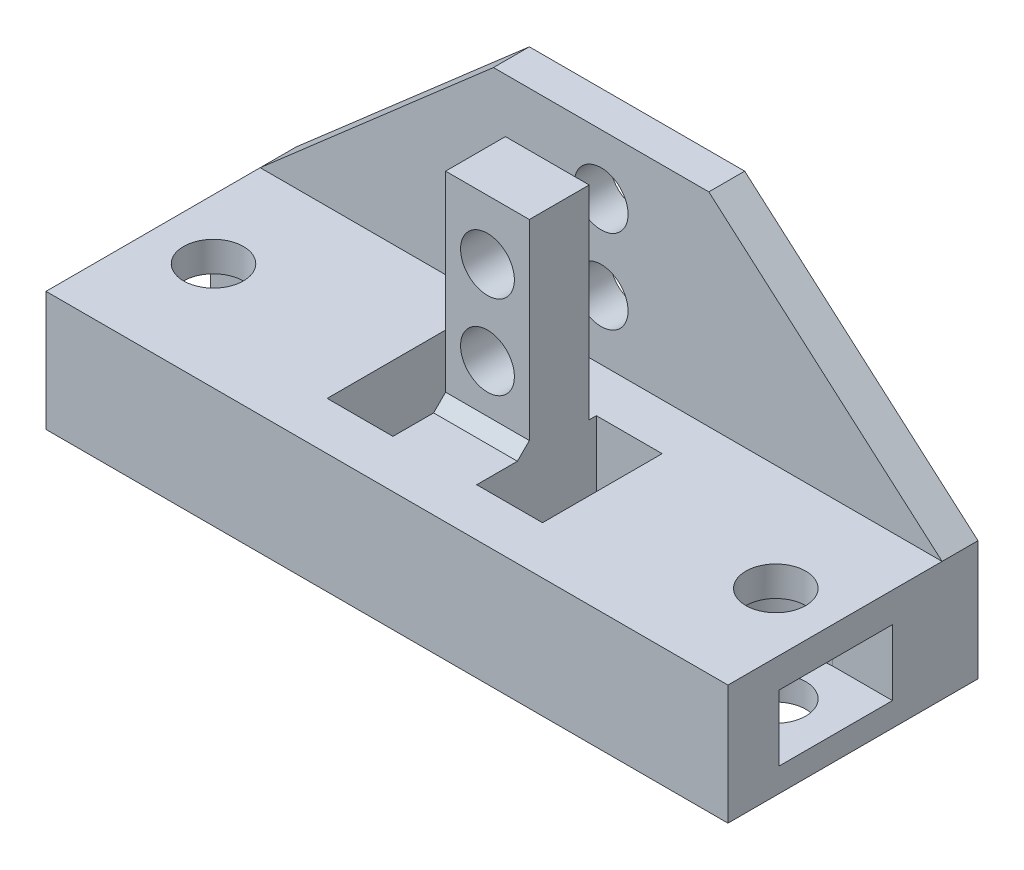
SolidWorks part; units mm, degrees
ref_plane "Plan de face" through (0, 0, 0) normal (0, 0, 1) x (1, 0, 0)
ref_plane "Plan de dessus" through (0, 0, 0) normal (0, 1, 0) x (1, 0, 0)
ref_plane "Plan de droite" through (0, 0, 0) normal (1, 0, 0) x (0, 0, -1)
sketch "Esquisse1" plane through (0, 0, 0) normal (0, 0, 1) x (1, 0, 0)
  line L0 (0, 17) -> (20, 17)
  line L1 (0, 0) -> (20, 0)
  line L2 (0, 0) -> (0, 25.6902)
  line L3 (0, 25.6902) -> (20, 25.6902)
  line L4 (20, 0) -> (20, 25.6902)
  circle A0 centre (10, 5) radius 2.1
  circle A1 centre (10, 12) radius 2.1
  dimension "D2" = 4.2
  dimension "D3" = 4.2
  dimension "D1" = 20
  dimension "D5" = 10
  dimension "D6" = 5
  dimension "D7" = 7
  dimension "D9" = 17
  dimension "D11" = 10
extrude "Boss.-Extru.1" add sketch "Esquisse1" along normal blind 5
sketch "Esquisse2" plane through (0, 0, 0) normal (0, -1, 0) x (1, 0, 0)
  line L0 (20, 5) -> (20, 0) construction
  line L1 (0, 0) -> (20, 0)
  line L2 (0, 0) -> (0, 5)
  line L3 (0, 5) -> (20, 5)
  line L4 (20, 0) -> (20, 5)
  line L5 (1, 5) -> (1, 0)
  line L6 (19, 5) -> (19, 0)
  line L7 (1, 3) -> (19, 3)
  line L9 (1, 0) -> (19, 0)
  line L10 (1, 0) -> (1, -5)
  line L11 (1, -5) -> (19, -5)
  line L12 (19, 0) -> (19, -5)
  line L13 (1, 0) -> (19, 0)
  line L14 (1, 0) -> (1, -0.6)
  line L15 (1, -0.6) -> (19, -0.6)
  line L16 (19, 0) -> (19, -0.6)
  point P11 (19, 2.5)
  dimension "D1" = 5
  dimension "D2" = 18
  dimension "D3" = 1
  dimension "D4" = 3
  dimension "D5" = 5
  dimension "D6" = 0.6
extrude "Boss.-Extru.3" add sketch "Esquisse2" along normal blind 10 contours L15 L10 L11 L12
sketch "Esquisse5" plane through (0, 0, 5) normal (0, 0, 1) x (1, 0, 0)
  line L0 (13.5, 17) -> (13.5, 0)
  line L1 (0, 17) -> (20, 17) construction
  line L2 (0, 0) -> (20, 0) construction
  line L3 (13.5, 0) -> (20, 0)
  line L4 (20, 0) -> (20, 17)
  line L5 (20, 0) -> (20, 17) construction
  line L6 (20, 17) -> (13.5, 17)
  line L8 (0, 0) -> (6.5, 0)
  line L9 (0, 0) -> (0, 17)
  line L10 (0, 17) -> (6.5, 17)
  line L11 (6.5, 0) -> (6.5, 17)
  dimension "D1" = 6.5
  dimension "D2" = 6.5
extrude "Enlèv. mat.-Extru.3" cut sketch "Esquisse5" against normal blind 18
sketch "Esquisse10" plane through (0, 0, 5) normal (0, 0, 1) x (1, 0, 0)
  line L1 (6.5, 0) -> (13.5, 0)
  line L2 (6.5, 0) -> (6.5, -10)
  line L3 (6.5, -10) -> (13.5, -10)
  line L4 (13.5, 0) -> (13.5, -10)
  dimension "D1" = 7
  dimension "D2" = 10
extrude "Boss.-Extru.6" add sketch "Esquisse10" against normal blind 10 and the other way blind 8.4
sketch "Esquisse11" plane through (0, 0, 0) normal (0, 1, 0) x (1, 0, 0)
  line L0 (6.5, 0.6) -> (6.5, 0) construction
  line L1 (6.5, 0) -> (13.5, 0)
  line L2 (6.5, 0) -> (6.5, 5)
  line L3 (6.5, 5) -> (13.5, 5)
  line L4 (13.5, 0) -> (13.5, 5)
  line L5 (6.5, 0) -> (13.5, 0) construction
  line L6 (1, 5) -> (19, 5) construction
  line L8 (13.5, 4.5) -> (6.5, 4.5)
  line L9 (13.5, 4.5) -> (13.5, 0)
  line L10 (13.5, 0) -> (6.5, 0)
  line L11 (6.5, 4.5) -> (6.5, 0)
  line L12 (6.5, 4.5) -> (13.5, 4.5)
  line L13 (6.5, 4.5) -> (6.5, 7.5)
  line L14 (6.5, 7.5) -> (13.5, 7.5)
  line L15 (13.5, 4.5) -> (13.5, 7.5)
  line L16 (6.5, 4.5) -> (1, 4.5)
  line L17 (6.5, 4.5) -> (6.5, 7.5)
  line L18 (6.5, 7.5) -> (1, 7.5)
  line L19 (1, 4.5) -> (1, 7.5)
  line L20 (13.5, 4.5) -> (19, 4.5)
  line L21 (13.5, 4.5) -> (13.5, 7.5)
  line L22 (13.5, 7.5) -> (19, 7.5)
  line L23 (19, 4.5) -> (19, 7.5)
  line M12 (19, 0.6) -> (19, 5)
  line M13 (19, 5) -> (1, 5)
  line M14 (1, 5) -> (1, 0.6)
  dimension "D1" = 7
  dimension "D2" = 4.5
  dimension "D3" = 3
  dimension "D4" = 5.5
  dimension "D5" = 5.5
extrude "Boss.-Extru.7" add sketch "Esquisse11" along normal blind 17 contours L19 L13 L18 M13 | L15 L14 L13 M13 | L23 L22 L15 M13 | L16 L2 M13 M14 | L8 L4 L2 M13 | L4 L20 M12 M13
sketch "Esquisse12" plane through (0, 0, 0) normal (0, -1, 0) x (1, 0, 0)
  line L5 (1, -5) -> (19, -5)
  line L6 (1, -5) -> (1, -7.5)
  line L7 (1, -7.5) -> (19, -7.5)
  line L8 (19, -5) -> (19, -7.5)
extrude "Boss.-Extru.8" add sketch "Esquisse12" along normal blind 10
sketch "Esquisse20" plane through (0, 0, 5) normal (0, 0, 1) x (1, 0, 0)
  circle A0 centre (10, 5) radius 2.25
  circle A1 centre (10, 12) radius 2.25
  dimension "D1" = 4.5
extrude "Enlèv. mat.-Extru.7" cut sketch "Esquisse20" against normal blind 18
sketch "Esquisse21" plane through (13.5, 0, 0) normal (1, 0, 0) x (0, 0, -1)
  line L0 (-13.4, -10) -> (0.6, -10) construction
  line L1 (-13.4, 0) -> (-9.4, 0)
  line L2 (-13.4, 0) -> (-13.4, -10)
  line L3 (-13.4, -10) -> (-9.4, -10)
  line L4 (-9.4, 0) -> (-9.4, -10)
  line L7 (0.6, 0) -> (7.5, 0)
  line L8 (0.6, 0) -> (0.6, -10)
  line L9 (0.6, -10) -> (7.5, -10)
  line L11 (7.5, 0) -> (7.5, -10)
  dimension "D1" = 4
  dimension "D2" = 6.9
extrude "Boss.-Extru.9" add sketch "Esquisse21" along normal blind 25
sketch "Esquisse22" plane through (0, 0, -0.6) normal (0, 0, 1) x (1, 0, 0)
  line L1 (38.5, -10) -> (13.5, -10) construction
  line L2 (38.5, 0) -> (19, 0)
  line L3 (38.5, 0) -> (38.5, -10)
  line L4 (38.5, -10) -> (19, -10)
  line L5 (19, 0) -> (19, -10)
  line L6 (13.5, 0) -> (13.5, -10) construction
  dimension "D1" = 5.5
extrude "Boss.-Extru.10" add sketch "Esquisse22" along normal up to surface (14 mm away) up to face at (22.5, -5, 13.4)
sketch "Esquisse24" plane through (0, 0, -7.5) normal (0, 0, -1) x (-1, 0, 0)
  line L0 (-38.5, 0) -> (-19, 0)
  line L2 (-19, 0) -> (-19, 17)
  line L5 (-19, 17) -> (-38.5, 0)
extrude "Boss.-Extru.11" add sketch "Esquisse24" against normal up to surface (3 mm away) up to face at (12.25, 12, -4.5)
ref_plane "Plan1" through (10, 0, 0) normal (-1, 0, 0) x (0, 0, 1)
mirror "Symétrie1" about plane through (10, 0, 0) normal (-1, 0, 0) of "Boss.-Extru.10", "Boss.-Extru.9", "Boss.-Extru.11"
chamfer "Chanfrein1" distance 1 angle 45 1 edges at (10, 0, 5)
sketch "Esquisse29" plane through (0, 0, 0) normal (0, 1, 0) x (1, 0, 0)
  line L0 (19, -9.4) -> (13.5, -9.4) construction
  line L1 (1, -9.4) -> (6.5, -9.4) construction
  line L2 (-18.5, 4.5) -> (-18.5, -13.4) construction
  line L3 (38.5, 4.5) -> (38.5, -13.4) construction
  circle A0 centre (-13.5, -4.4) radius 2.5
  circle A1 centre (33.5, -4.4) radius 2.5
  point P8 (0, 0)
  point P9 (0, 0)
  dimension "D3" = 5
  dimension "D4" = 5
  dimension "D5" = 5
  dimension "D1" = 5
  dimension "D2" = 5
  dimension "D6" = 5
extrude "Enlèv. mat.-Extru.11" cut sketch "Esquisse29" against normal blind 10
sketch "Esquisse30" plane through (0, -10, 0) normal (0, -1, 0) x (-1, 0, 0)
  line L1 (13.5, -9.15) -> (18.5, -9.15)
  line L2 (18.5, -13.4) -> (18.5, 7.5) construction
  line L3 (18.5, -9.15) -> (18.5, 0.35)
  line L4 (18.5, 0.35) -> (13.5, 0.35)
  circle A0 centre (13.5, -4.4) radius 4.75
  circle M8 centre (13.5, -4.4) radius 2.5
  line M15 (18.5, -13.4) -> (18.5, 7.5)
  dimension "D1" = 9.5
extrude "Enlèv. mat.-Extru.12" cut sketch "Esquisse30" against normal blind 5.5 from offset 2 contours A0 M8 | A0 L1 L4 M15 offset against normal yes
mirror "Symétrie3" about plane through (10, 0, 0) normal (-1, 0, 0) of "Enlèv. mat.-Extru.12"
